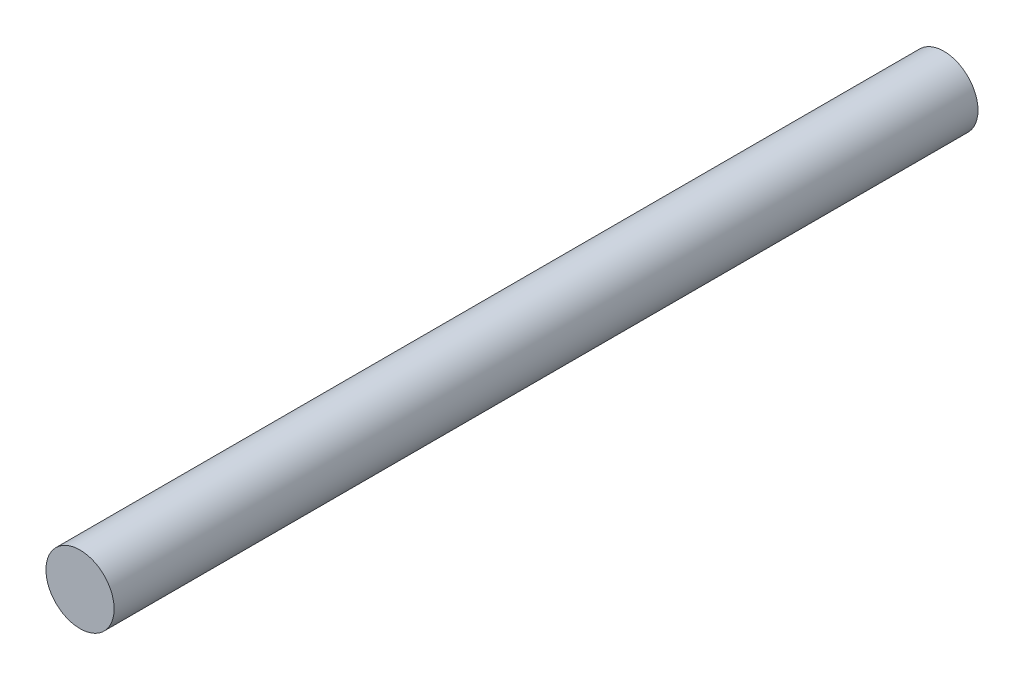
SolidWorks part; units mm, degrees
ref_plane "前基準面" through (0, 0, 0) normal (0, 0, 1) x (1, 0, 0)
ref_plane "上基準面" through (0, 0, 0) normal (0, 1, 0) x (1, 0, 0)
ref_plane "右基準面" through (0, 0, 0) normal (1, 0, 0) x (0, 0, -1)
sketch "草圖1" plane through (0, 0, 0) normal (0, 0, 1) x (1, 0, 0)
  circle A0 centre (-16.1371, 5.9745) radius 1.5
  dimension "D1" = 3
extrude "填料-伸長1" add sketch "草圖1" along normal blind 38
